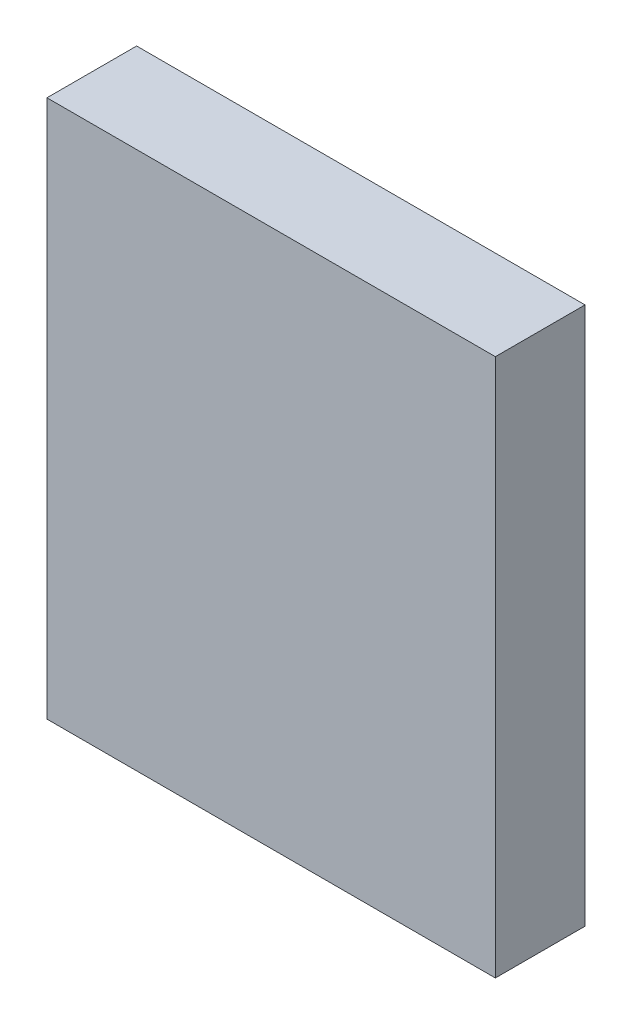
SolidWorks part; units mm, degrees
ref_plane "前视基准面" through (0, 0, 0) normal (0, 0, 1) x (1, 0, 0)
ref_plane "上视基准面" through (0, 0, 0) normal (0, 1, 0) x (1, 0, 0)
ref_plane "右视基准面" through (0, 0, 0) normal (1, 0, 0) x (0, 0, -1)
ref_plane "基准面1" through (0, 0, 12) normal (0, 0, 1) x (1, 0, 0)
sketch "草图1" plane through (0, 0, 12) normal (0, 0, 1) x (1, 0, 0)
  line L0 (0, 60) -> (0, 0)
  line L1 (0, 0) -> (50, 0)
  line L2 (50, 0) -> (50, 60)
  line L3 (50, 60) -> (0, 60)
extrude "凸台-拉伸1" add sketch "草图1" against normal blind 10
